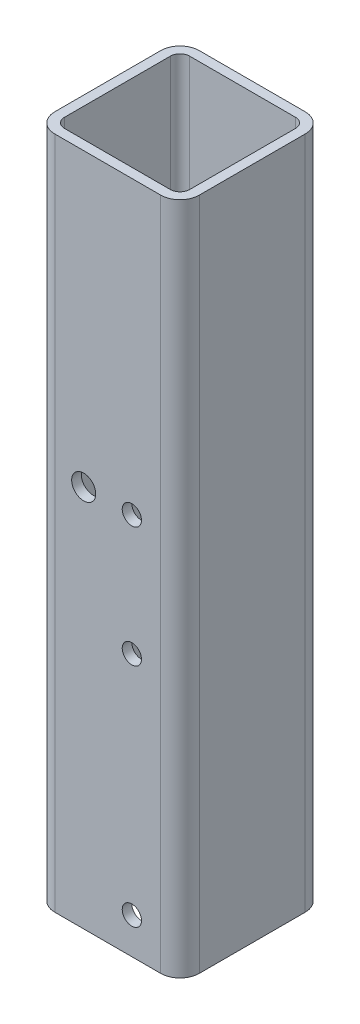
SolidWorks part; units mm, degrees
ref_plane "前视基准面" through (0, 0, 0) normal (0, 0, 1) x (1, 0, 0)
ref_plane "上视基准面" through (0, 0, 0) normal (0, 1, 0) x (1, 0, 0)
ref_plane "右视基准面" through (0, 0, 0) normal (1, 0, 0) x (0, 0, -1)
sketch "草图2" plane through (0, 0, 0) normal (0, 1, 0) x (1, 0, 0)
  line L0 (4, 2) -> (26, 2)
  line L1 (4, 0) -> (26, 0)
  line L2 (0, 4) -> (0, 26)
  line L3 (4, 30) -> (26, 30)
  line L4 (30, 4) -> (30, 26)
  line L5 (28, 4) -> (28, 26)
  line L6 (4, 28) -> (26, 28)
  line L7 (2, 4) -> (2, 26)
  arc A0 (4, 0) -> (0, 4) centre (4, 4) cw
  arc A1 (26, 0) -> (30, 4) centre (26, 4) ccw
  arc A2 (26, 30) -> (30, 26) centre (26, 26) cw
  arc A3 (0, 26) -> (4, 30) centre (4, 26) cw
  arc A4 (26, 2) -> (28, 4) centre (26, 4) ccw
  arc A5 (26, 28) -> (28, 26) centre (26, 26) cw
  arc A6 (2, 26) -> (4, 28) centre (4, 26) cw
  arc A7 (4, 2) -> (2, 4) centre (4, 4) cw
  point P7 (0, 0)
  point P10 (30, 0)
  point P13 (30, 30)
  point P16 (0, 30)
  dimension "D3" = 4
  dimension "D1" = 30
  dimension "D2" = 30
  dimension "D4" = 2
extrude "凸台-拉伸1" add sketch "草图2" along normal mid plane 140
sketch "草图3" plane through (0, 0, 0) normal (0, 0, 1) x (1, 0, 0)
  line L0 (0, 0) -> (30, 0) construction
  line L1 (30, 70) -> (30, -70) construction
  line L2 (4, -70) -> (26, -70) construction
  circle A0 centre (10, 9.5) radius 2.5
  circle A1 centre (20, 9.5) radius 2
  circle A2 centre (20, -15.5) radius 2
  circle A3 centre (20, -62.5) radius 2
  point P13 (-11.2505, 9.5)
  point P17 (0, 0)
  point P18 (0, 0)
  point P19 (0, 0)
  point P20 (0, 0)
  dimension "D1" = 4
  dimension "D2" = 5
  dimension "D3" = 25
  dimension "D4" = 10
  dimension "D5" = 10
  dimension "D6" = 47
  dimension "D8" = 7.5
extrude "切除-拉伸1" cut sketch "草图3" against normal through all
